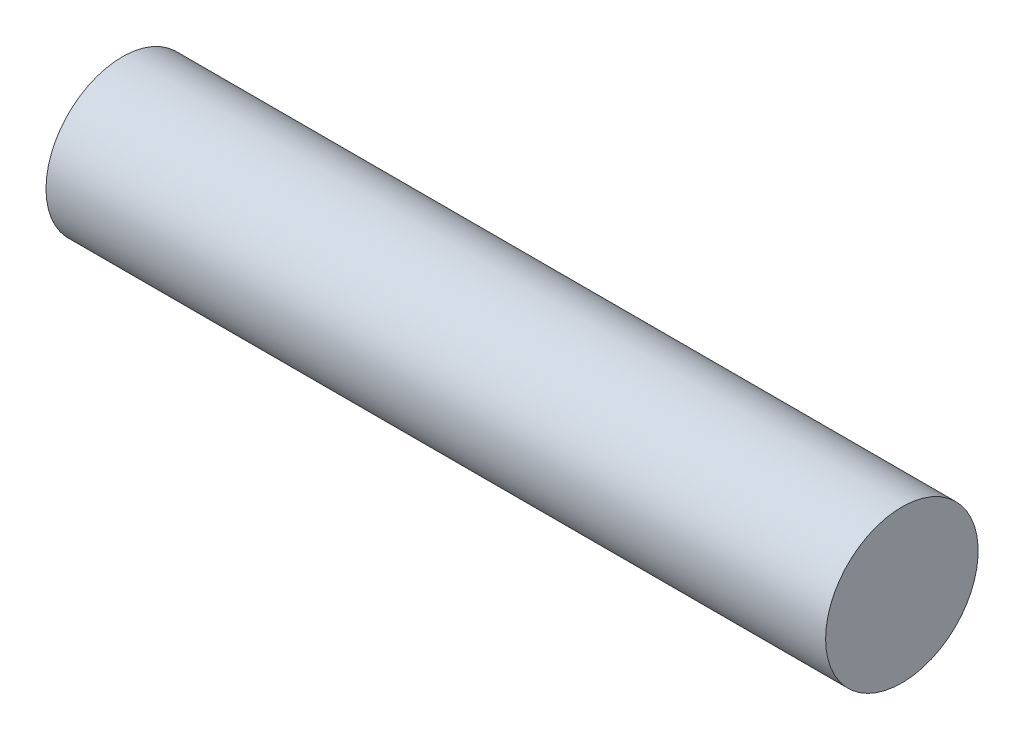
SolidWorks part; units mm, degrees
ref_plane "前视基准面" through (0, 0, 0) normal (0, 0, 1) x (1, 0, 0)
ref_plane "上视基准面" through (0, 0, 0) normal (0, 1, 0) x (1, 0, 0)
ref_plane "右视基准面" through (0, 0, 0) normal (1, 0, 0) x (0, 0, -1)
other "Configuration Table"
sketch "草图1" plane through (0, 0, 0) normal (0, 0, 1) x (1, 0, 0)
  line L0 (0, 0) -> (40.0305, 0) construction
  line L1 (0, 0) -> (0, 9)
  line L2 (0, 9) -> (92, 9)
  line L3 (92, 9) -> (92, 0)
  line L4 (0, 0) -> (92, 0)
  dimension "D1" = 9
  dimension "D2" = 92
revolve "旋转1" add sketch "草图1" angle 360 about L0
